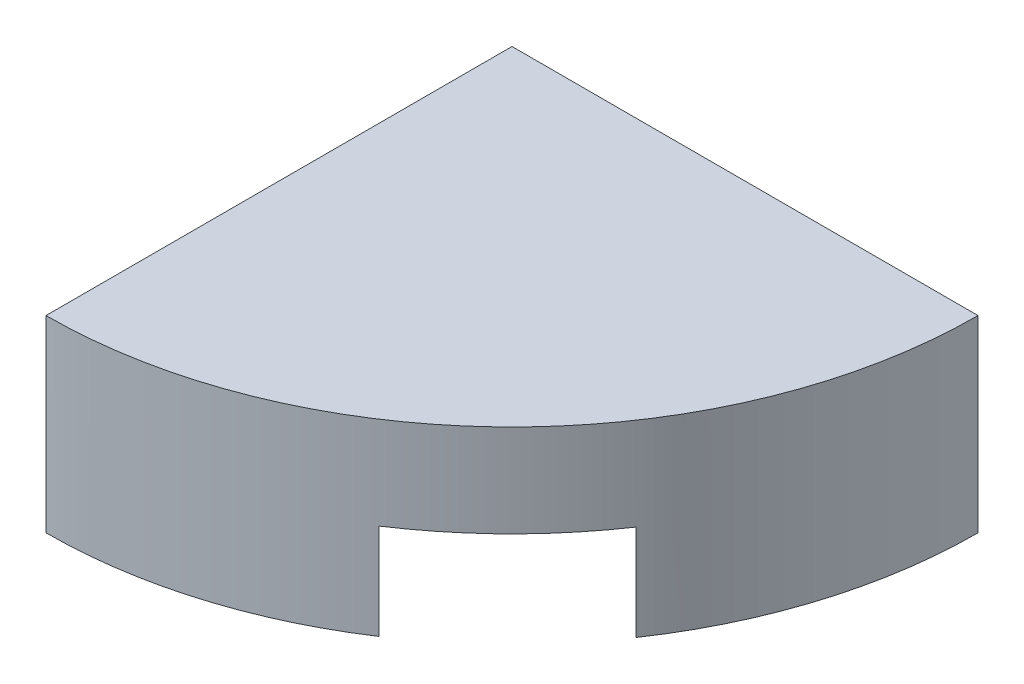
SolidWorks part; units mm, degrees
ref_plane "Front Plane" through (0, 0, 0) normal (0, 0, 1) x (1, 0, 0)
ref_plane "Top Plane" through (0, 0, 0) normal (0, 1, 0) x (1, 0, 0)
ref_plane "Right Plane" through (0, 0, 0) normal (1, 0, 0) x (0, 0, -1)
sketch "Sketch1" plane through (0, 0, 0) normal (0, 1, 0) x (1, 0, 0)
  line L0 (0, 0) -> (0, -7.8)
  line L1 (0, 0) -> (7.8, 0)
  arc A0 (0, -7.8) -> (7.8, 0) centre (0, 0) ccw
  dimension "D1" = 7.8
extrude "Boss-Extrude1" add sketch "Sketch1" against normal blind 3.15
shell "Shell1" thickness 1.55
sketch "Sketch2" plane through (0, -1.55, 0) normal (0, -1, 0) x (1, 0, 0)
  line L0 (7.8, 0) -> (0, 0) construction
  line L1 (0, 0) -> (0, 7.8) construction
  circle A0 centre (4.031, 4.0883) radius 2.4404
  dimension "D1" = 4.8809
  dimension "D2" = 4.0883
  dimension "D3" = 4.031
extrude "Cut-Extrude1" cut sketch "Sketch2" along normal up to surface (1.6 mm away) up to face at (3.2573, -3.15, 3.2573)
sketch "Sketch3" plane through (0, -1.55, 0) normal (0, -1, 0) x (1, 0, 0)
  line L0 (7.8, 0) -> (0, 0) construction
  line L1 (0, 0) -> (0, 7.8) construction
  circle A0 centre (4.03, 4.09) radius 0.6922
  dimension "D3" = 1.3844
  dimension "D1" = 4.09
  dimension "D2" = 4.03
